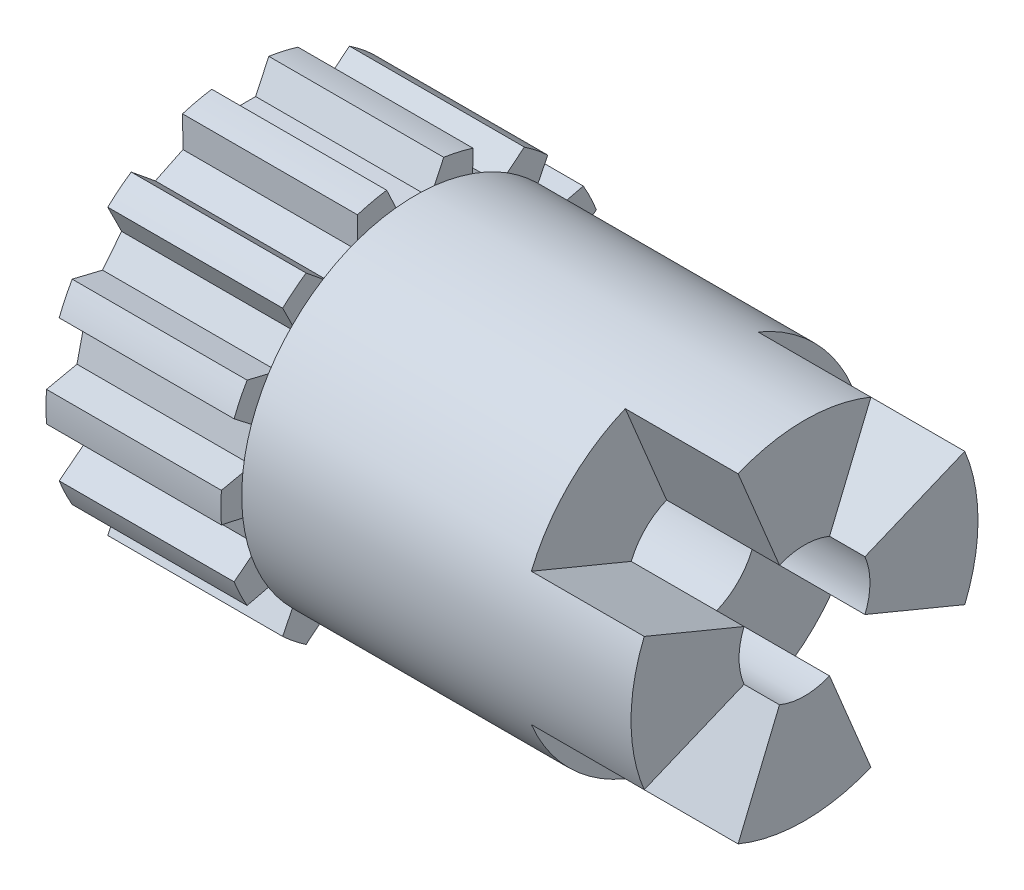
SolidWorks part; units mm, degrees
ref_plane "Front Plane" through (0, 0, 0) normal (0, 0, 1) x (1, 0, 0)
ref_plane "Top Plane" through (0, 0, 0) normal (0, 1, 0) x (1, 0, 0)
ref_plane "Right Plane" through (0, 0, 0) normal (1, 0, 0) x (0, 0, -1)
sketch "Sketch2" plane through (0, 0, 0) normal (1, 0, 0) x (0, 0, -1)
  line L3 (0, 0) -> (0, 3.7084) construction
  line L6 (0, -4.2164) -> (0, -4.5339) construction
  line L7 (-0.5715, 4.1775) -> (-0.3452, 3.6923)
  line L8 (0.5715, 4.1775) -> (0.3452, 3.6923)
  line L9 (-0.5715, 4.1775) -> (-0.6416, 4.3278)
  line L10 (0.5715, 4.1775) -> (0.6416, 4.3278)
  line L12 (-0.3452, 3.6923) -> (0.3452, 3.6923)
  line L14 (0, 4.2164) -> (0, 4.5339) construction
  line L15 (0, 0) -> (0, -1.143) construction
  circle A0 centre (0, 0) radius 4.5339 construction
  circle A1 centre (0, 0) radius 3.7084 construction
  circle A2 centre (0, 0) radius 4.2164 construction
  arc A7 (0.6416, 4.3278) -> (-0.6416, 4.3278) centre (0, 0) ccw
  point P5 (0, 4.3751)
  dimension "D3" = 0.3175
  dimension "D1" = 50
sketch "Sketch1" plane through (0, 0, 0) normal (0, 0, 1) x (1, 0, 0)
  line L0 (-5.5626, 0) -> (5.5626, 0) construction
  line L1 (-5.5626, 1.5875) -> (5.5626, 1.5875)
  line L2 (-5.5626, 1.5875) -> (-5.5626, 6.731)
  line L3 (-5.5626, 6.731) -> (-0.5969, 6.731)
  line L4 (-0.5969, 6.731) -> (0.4572, 5.6769)
  line L5 (0.4572, 5.6769) -> (0.4572, 4.5339)
  line L6 (0.4572, 4.5339) -> (4.5212, 4.5339)
  line L7 (4.5212, 4.5339) -> (4.5212, 5.1054)
  line L8 (4.5212, 4.5339) -> (5.5626, 4.5339) construction
  line L9 (5.0419, 6.731) -> (5.5626, 6.731)
  line L10 (5.5626, 6.731) -> (5.5626, 1.5875)
  line L11 (5.0419, 4.5339) -> (5.0419, 6.731) construction
  line L12 (-3.0797, 6.731) -> (-3.0797, 1.5875) construction
  arc A0 (4.5212, 5.1054) -> (5.0419, 6.731) centre (7.3191, 5.1054) cw
  dimension "Bore Size" = 3.175
  dimension "Overall Width" = 11.1252
  dimension "Inside Width" = 4.064
  dimension "Outside Width" = 5.1054
  dimension "Hub Dia" = 13.462
  dimension "OD" = 13.462
  dimension "D1" = 45
  dimension "D2" = 9.0678
  dimension "D3" = 1.143
  dimension "D4" = 0.5715
revolve "Revolve1" add sketch "Sketch1" angle 360 mid plane about L0
sketch "Sketch4" plane through (0.4572, 0, 0) normal (1, 0, 0) x (0, 0, -1)
  circle A0 centre (0, 0) radius 4.3751
  circle A1 centre (0, 0) radius 4.5339 construction
  circle A2 centre (0, 0) radius 4.5339
extrude "Cut-Extrude2" cut sketch "Sketch4" along normal up to surface (4.064 mm away) up to face at (4.5212, 0, 4.5339)
sketch "Sketch3" plane through (0.4572, 0, 0) normal (1, 0, 0) x (0, 0, -1)
  line L2 (-0.5715, 4.1775) -> (-0.3452, 3.6923) construction
  line L3 (-0.3452, 3.6923) -> (0.3452, 3.6923) construction
  line L4 (0.5715, 4.1775) -> (0.3452, 3.6923) construction
  line L5 (-0.6416, 4.3278) -> (-0.3452, 3.6923)
  line L6 (-0.3452, 3.6923) -> (0.3452, 3.6923)
  line L7 (0.6416, 4.3278) -> (0.3452, 3.6923)
  arc A1 (0.6416, 4.3278) -> (-0.6416, 4.3278) centre (0, 0) ccw construction
  arc A2 (0.6416, 4.3278) -> (-0.6416, 4.3278) centre (0, 0) ccw
extrude "Cut-Extrude1" cut sketch "Sketch3" along normal up to surface (4.064 mm away)
pattern_circular "CirPattern1" count 14 over 360 about axis through (0, 0, 0) along (1, 0, 0) of "Cut-Extrude1"
sketch "Sketch5" plane through (0, 0, 0) normal (0, 0, 1) x (1, 0, 0)
  line L1 (4.5212, 5.1054) -> (4.5212, -5.1054) construction
  point P0 (4.5212, 0)
sketch "Sketch6" plane through (0, 0, 0) normal (0, 1, 0) x (1, 0, 0)
  line L0 (-5.5626, 0) -> (-4.1402, 0) construction
  line L1 (-5.5626, 6.731) -> (-5.5626, -6.731) construction
  line L2 (0.4572, 0) -> (-0.9652, 0) construction
  line L3 (0.4572, -0.3452) -> (0.4572, 0.3452) construction
  circle A0 centre (-2.5527, 0) radius 1.5875
  dimension "D1" = 3.175
extrude "Cut-Extrude3" cut sketch "Sketch6" along normal through all
sketch "Sketch7" plane through (0, 0, 0) normal (0, 0, 1) x (1, 0, 0)
  line L0 (-3.7211, 6.731) -> (-2.5527, 6.731)
  line L1 (-3.9751, 6.477) -> (-3.9751, 2.2225)
  line L2 (-3.9751, 2.2225) -> (-3.7211, 1.9685)
  line L3 (-3.7211, 1.9685) -> (-2.5527, 1.9685)
  line L4 (-2.5527, 1.9685) -> (-2.5527, 6.731) construction
  line L6 (-3.9751, 6.477) -> (-3.7211, 6.731)
  line L7 (-5.5626, 6.731) -> (-0.5969, 6.731) construction
  line L8 (-2.5527, 6.731) -> (-2.5527, 1.9685)
  point P0 (-3.9751, 6.731)
  point P4 (-3.9751, 1.9685)
  dimension "D1" = 2.8448
  dimension "D2" = 0.381
revolve "Revolve2" add sketch "Sketch7" angle 360 mid plane about L4
sketch "Sketch8" plane through (0, 6.731, 0) normal (0, 1, 0) x (1, 0, 0)
  line L1 (-2.5527, 0.8212) -> (-3.2639, 0.4106)
  line L2 (-3.2639, 0.4106) -> (-3.2639, -0.4106)
  line L3 (-3.2639, -0.4106) -> (-2.5527, -0.8212)
  line L4 (-2.5527, -0.8212) -> (-1.8415, -0.4106)
  line L5 (-1.8415, -0.4106) -> (-1.8415, 0.4106)
  line L6 (-1.8415, 0.4106) -> (-2.5527, 0.8212)
  circle A0 centre (-2.5527, 0) radius 0.7112 construction
  dimension "D1" = 1.4224
extrude "Cut-Extrude4" cut sketch "Sketch8" against normal blind 1.016
pattern_circular "CirPattern2" [suppressed] count 2 over 90
pattern_circular "CirPattern3" [suppressed] count 2 over 90
sketch "Sketch9" plane through (5.5626, 0, 0) normal (1, 0, 0) x (0, 0, -1)
  circle A0 centre (0, 0) radius 6.985
  dimension "D1" = 13.97
extrude "Cut-Extrude5" cut sketch "Sketch9" against normal up to surface (1.0414 mm away)
sketch "Sketch10" plane through (-5.5626, 0, 0) normal (-1, 0, 0) x (0, 0, 1)
  circle A0 centre (0, 0) radius 6.985
  dimension "D1" = 13.97
extrude "Cut-Extrude6" cut sketch "Sketch10" against normal offset from surface (6.1468 mm away) 3.937 up to face at (4.5212, 0, 0)
ref_plane "Plane1" through (0.5842, 0.3375, -4.3621) normal (-1, 0, 0) x (0, 0, 1)
sketch "Sketch12" plane through (4.5212, 0, 0) normal (1, 0, 0) x (0, 0, -1)
  circle A0 centre (0, 0) radius 1.5875
  circle A1 centre (0, 0) radius 1.5875 construction
  circle A2 centre (0, 0) radius 1.4732
  dimension "D1" = 2.9464
extrude "Boss-Extrude1" add sketch "Sketch12" against normal up to surface (3.937 mm away) up to face at (0.5842, 0, 0)
sketch "Sketch13" plane through (4.5212, 0, 0) normal (1, 0, 0) x (0, 0, -1)
  circle A0 centre (0, 0) radius 3.9053
  circle A1 centre (0, 0) radius 1.4732
  circle A2 centre (0, 0) radius 1.4732 construction
  dimension "D1" = 7.8105
extrude "Boss-Extrude2" add sketch "Sketch13" along normal blind 6.223
sketch "Sketch14" plane through (10.7442, 0, 0) normal (1, 0, 0) x (0, 0, -1)
  line L0 (0, 0) -> (3.9053, 0) construction
  line L1 (1.3611, -0.5638) -> (3.608, -1.4945)
  line L2 (3.608, 1.4945) -> (1.3611, 0.5638)
  arc A0 (3.8802, -0.4412) -> (3.8802, 0.4412) centre (0, 0) ccw construction
  arc A1 (3.608, 1.4945) -> (3.608, -1.4945) centre (0, 0) cw
  arc A2 (1.3611, 0.5638) -> (1.3611, -0.5638) centre (0, 0) cw
  circle A3 centre (0, 0) radius 1.4732 construction
  circle A4 centre (0, 0) radius 3.9053 construction
  point P15 (1.4732, 0)
  point P17 (3.9053, 0)
  dimension "D1" = 45
extrude "Boss-Extrude3" add sketch "Sketch14" along normal blind 2.54
pattern_circular "CirPattern4" count 4 over 360 about axis through (-3.9059, 0, 0) along (1, 0, 0) of "Boss-Extrude3"
equation "\"D3@Sketch2\" = (\"hs@Sketch2\"-\"ht@Sketch2\")/2"
equation "\"D2@Sketch1\" = \"PD@Sketch2\""
equation "\"D3@Sketch1\" = \"hs@Sketch2\""
equation "\"D4@Sketch1\" = \"D3@Sketch1\"/2"
